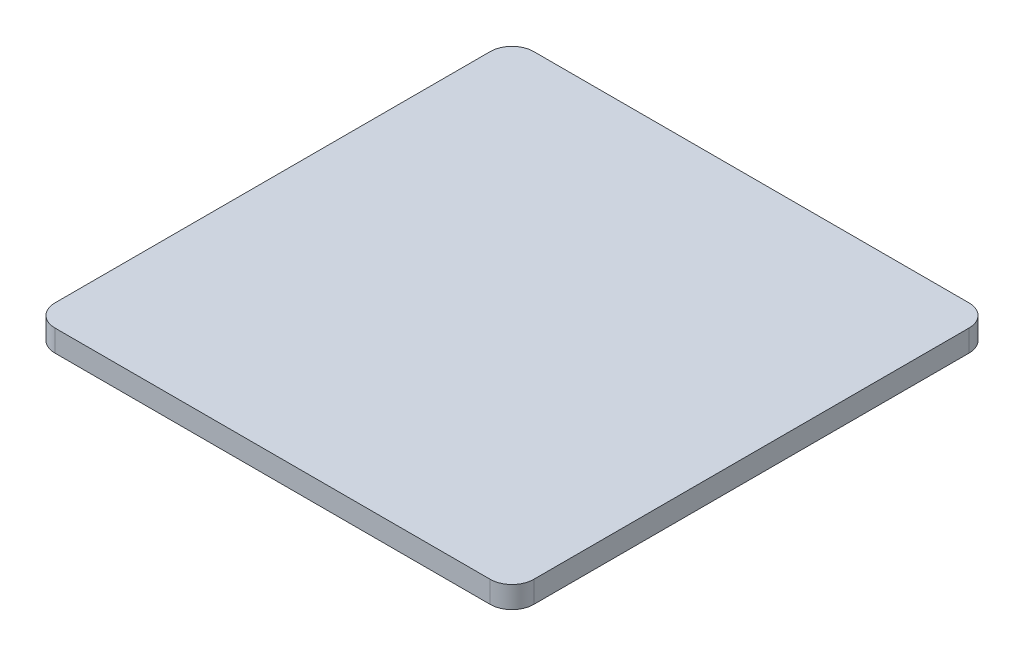
SolidWorks part; units mm, degrees
ref_plane "Front Plane" through (0, 0, 0) normal (0, 0, 1) x (1, 0, 0)
ref_plane "Top Plane" through (0, 0, 0) normal (0, 1, 0) x (1, 0, 0)
ref_plane "Right Plane" through (0, 0, 0) normal (1, 0, 0) x (0, 0, -1)
sketch "Sketch1" plane through (0, 0, 0) normal (0, 1, 0) x (1, 0, 0)
  line L1 (-110, -110) -> (110, -110)
  line L2 (-110, -110) -> (-110, 110)
  line L3 (-110, 110) -> (110, 110)
  line L4 (110, -110) -> (110, 110)
  line L5 (-110, -110) -> (110, 110) construction
  line L6 (-110, 110) -> (110, -110) construction
  point P0 (0, 0)
  dimension "D1" = 220
extrude "Boss-Extrude1" add sketch "Sketch1" along normal blind 10
fillet "Fillet1" radius 10 4 edges at (-110, 5, 110) (110, 5, 110) (110, 5, -110) (-110, 5, -110)
